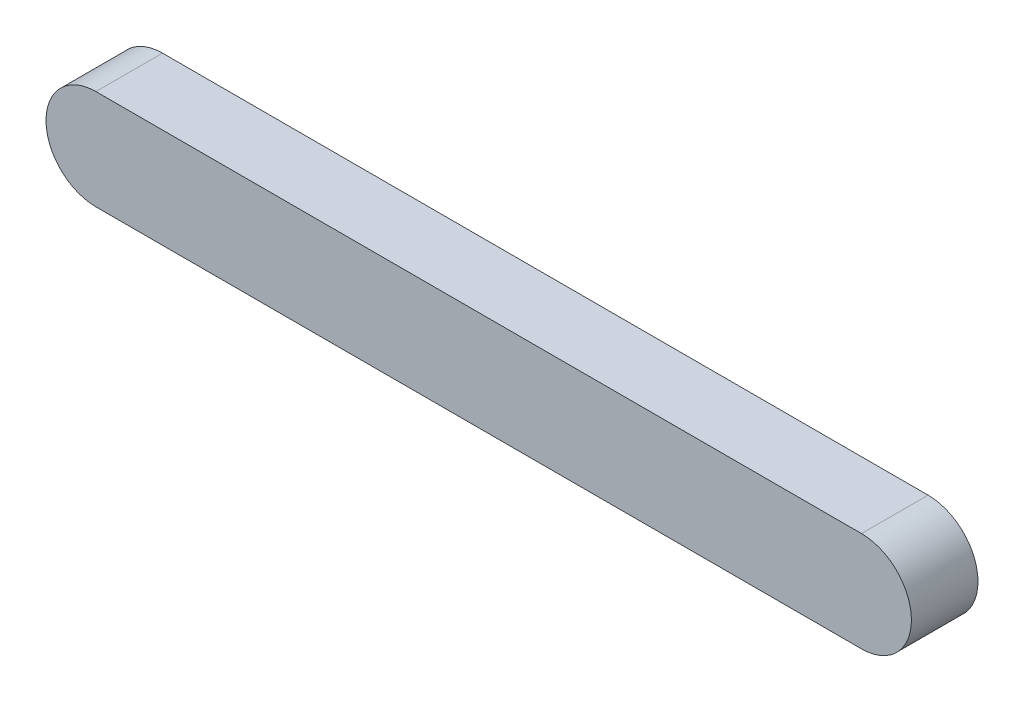
SolidWorks part; units mm, degrees
ref_plane "前视基准面" through (0, 0, 0) normal (0, 0, 1) x (1, 0, 0)
ref_plane "上视基准面" through (0, 0, 0) normal (0, 1, 0) x (1, 0, 0)
ref_plane "右视基准面" through (0, 0, 0) normal (1, 0, 0) x (0, 0, -1)
other "Configuration Table"
sketch "草图1" plane through (0, 0, 0) normal (0, 0, 1) x (1, 0, 0)
  line L0 (115, 0) -> (0, 0) construction
  line L1 (115, -7.5) -> (0, -7.5)
  line L2 (115, 7.5) -> (0, 7.5)
  arc A0 (115, -7.5) -> (115, 7.5) centre (115, 0) ccw
  arc A1 (0, 7.5) -> (0, -7.5) centre (0, 0) ccw
  point P0 (57.5, 0)
  dimension "D1" = 115
  dimension "D2" = 15
extrude "凸台-拉伸1" add sketch "草图1" along normal blind 10
